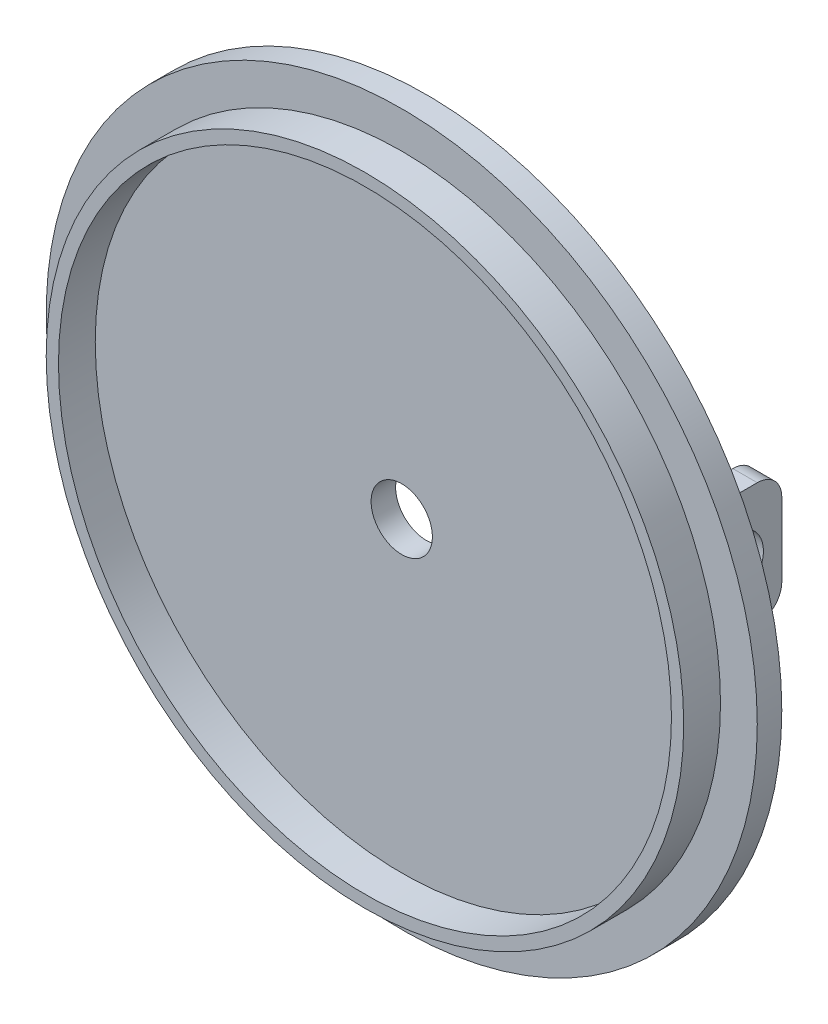
SolidWorks part; units mm, degrees
ref_plane "Front Plane" through (0, 0, 0) normal (0, 0, 1) x (1, 0, 0)
ref_plane "Top Plane" through (0, 0, 0) normal (0, 1, 0) x (1, 0, 0)
ref_plane "Right Plane" through (0, 0, 0) normal (1, 0, 0) x (0, 0, -1)
sketch "Sketch1" plane through (0, 0, 0) normal (0, 0, 1) x (1, 0, 0)
  circle A0 centre (0, 0) radius 29
  circle A1 centre (0, 0) radius 2.5
  dimension "D1" = 58
  dimension "D2" = 5
extrude "Boss-Extrude1" add sketch "Sketch1" along normal blind 2
sketch "Sketch2" plane through (0, 0, 2) normal (0, 0, 1) x (1, 0, 0)
  circle A0 centre (0, 0) radius 26
  circle A1 centre (0, 0) radius 25
  dimension "D1" = 52
  dimension "D2" = 50
extrude "Boss-Extrude2" add sketch "Sketch2" along normal blind 3
sketch "Sketch3" plane through (0, 0, 0) normal (0, 0, -1) x (-1, 0, 0)
  line L0 (-16, 7.5) -> (-16, -7.5) construction
  line L1 (-13.75, 7.5) -> (-13.75, -7.5)
  line L2 (-18.25, 7.5) -> (-18.25, -7.5)
  line L3 (16, 7.5) -> (16, -7.5) construction
  line L4 (18.25, 7.5) -> (18.25, -7.5)
  line L5 (13.75, 7.5) -> (13.75, -7.5)
  arc A0 (-13.75, 7.5) -> (-18.25, 7.5) centre (-16, 7.5) ccw
  arc A1 (-18.25, -7.5) -> (-13.75, -7.5) centre (-16, -7.5) ccw
  arc A2 (18.25, 7.5) -> (13.75, 7.5) centre (16, 7.5) ccw
  arc A3 (13.75, -7.5) -> (18.25, -7.5) centre (16, -7.5) ccw
  point P2 (-16, 0)
  point P7 (16, 0)
  dimension "D5" = 2.25
  dimension "D6" = 2.25
  dimension "D1" = 15
  dimension "D2" = 0
  dimension "D3" = 0
  dimension "D4" = 15
  dimension "D7" = 16
  dimension "D8" = 16
extrude "Boss-Extrude3" add sketch "Sketch3" along normal blind 2
sketch "Sketch4" plane through (0, 0, -2) normal (0, 0, -1) x (-1, 0, 0)
  line L0 (0, 15.7217) -> (0, -13.3509) construction
  line L1 (-17, 5.0754) -> (-15, 5.0754)
  line L2 (-17, 5.0754) -> (-17, -4.9246)
  line L3 (-17, -4.9246) -> (-15, -4.9246)
  line L4 (-15, 5.0754) -> (-15, -4.9246)
  line L5 (-17, 5.0754) -> (-15, -4.9246) construction
  line L6 (-17, -4.9246) -> (-15, 5.0754) construction
  line L7 (17, -4.9246) -> (15, -4.9246)
  line L8 (15, 5.0754) -> (15, -4.9246)
  line L9 (17, 5.0754) -> (15, 5.0754)
  line L10 (17, 5.0754) -> (17, -4.9246)
  point P0 (-16, 0.0754)
  point P12 (0, 0)
  dimension "D1" = 2
  dimension "D2" = 10
  dimension "D3" = 16
extrude "Boss-Extrude4" add sketch "Sketch4" along normal blind 10
fillet "Fillet1" radius 2 4 edges at (16, 5.0754, -12) (-16, 5.0754, -12) (-16, -4.9246, -12) (16, -4.9246, -12)
sketch "Sketch5" plane through (-17, 0, 0) normal (-1, 0, 0) x (0, 0, 1)
  circle A0 centre (-8, 0) radius 2.5
  dimension "D1" = 5
  dimension "D2" = 8
extrude "Cut-Extrude1" cut sketch "Sketch5" against normal through all
